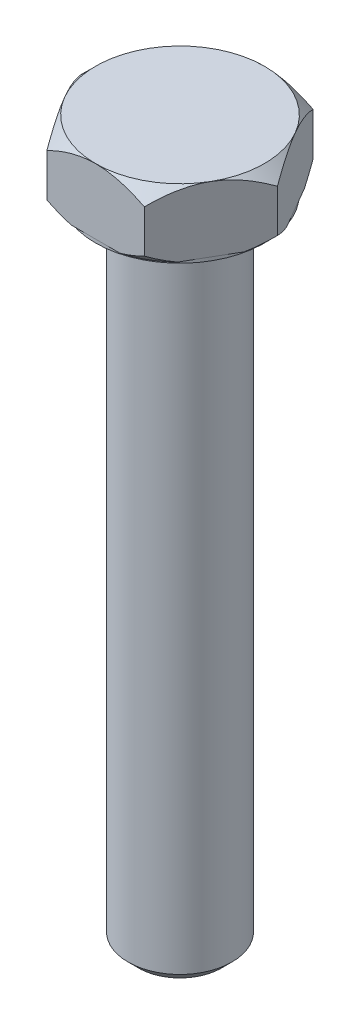
SolidWorks part; units mm, degrees
material "Cast Stainless Steel"
ref_plane "Front Plane" through (0, 0, 0) normal (0, 0, 1) x (1, 0, 0)
ref_plane "Top Plane" through (0, 0, 0) normal (0, 1, 0) x (1, 0, 0)
ref_plane "Right Plane" through (0, 0, 0) normal (1, 0, 0) x (0, 0, -1)
sketch "Sketch1" plane through (0, 0, 0) normal (0, 1, 0) x (1, 0, 0)
  line L0 (0, 0) -> (7.5056, 0) construction
  line L1 (7.5056, 0) -> (3.7528, 6.5)
  line L2 (3.7528, 6.5) -> (-3.7528, 6.5)
  line L3 (-3.7528, 6.5) -> (-7.5056, 0)
  line L4 (-7.5056, 0) -> (-3.7528, -6.5)
  line L5 (-3.7528, -6.5) -> (3.7528, -6.5)
  line L6 (3.7528, -6.5) -> (7.5056, 0)
  circle A0 centre (0, 0) radius 6.5 construction
  dimension "D1" = 13
extrude "Boss-Extrude1" add sketch "Sketch1" against normal blind 5.3
sketch "Sketch4" plane through (0, 0, 0) normal (1, 0, 0) x (0, 0, -1)
  line L0 (-6.5, 0) -> (-8.15, 0)
  line L1 (-8.15, 0) -> (-8.15, -1.65)
  line L2 (-8.15, -1.65) -> (-6.5, 0)
  line L3 (-6.5, -2.65) -> (6.5, -2.65) construction
  line L4 (-8.15, -3.65) -> (-6.5, -5.3)
  line L5 (-8.15, -5.3) -> (-8.15, -3.65)
  line L6 (-6.5, -5.3) -> (-8.15, -5.3)
  line L7 (0, 0) -> (0, -2.65) construction
  dimension "D1" = 45
  dimension "D2" = 2.65
  dimension "D3" = 1.65
  dimension "D4" = 13
revolve "Cut-Revolve1" cut sketch "Sketch4" angle 360 about L7
sketch "Sketch2" plane through (0, -5.3, 0) normal (0, -1, 0) x (1, 0, 0)
  circle A0 centre (0, 0) radius 6.5
  dimension "D1" = 13
extrude "Cut-Extrude1" cut sketch "Sketch2" against normal blind 0.265 flip side to cut
sketch "Sketch3" plane through (0, -5.3, 0) normal (0, -1, 0) x (1, 0, 0)
  circle A0 centre (0, 0) radius 4
  dimension "D1" = 8
extrude "Boss-Extrude2" add sketch "Sketch3" along normal blind 50
chamfer "Chamfer1" distance 0.8 angle 45 1 edges at (0, -55.3, -4)
equation "\"k\"= 5.3"
equation "\"e\"= 14.38"
equation "\"S\"= 13"
equation "\"L\"=50"
equation "\"D1@Sketch1\"=\"S\""
equation "\"D1@Boss-Extrude1\"=\"k\""
equation "\"D1@Sketch2\"=\"S\""
equation "\"D1@Cut-Extrude1\"=\"k\"/20"
equation "\"d\"= 8"
equation "\"D1@Sketch3\"=\"d\""
equation "\"D1@Boss-Extrude2\"=\"L\""
equation "\"D2@Sketch4\"=\"k\"/2"
equation "\"D3@Sketch4\"=\"D2@Sketch4\"-1"
equation "\"D4@Sketch4\"=\"S\""
equation "\"D1@Chamfer1\"=\"d\"/10"
